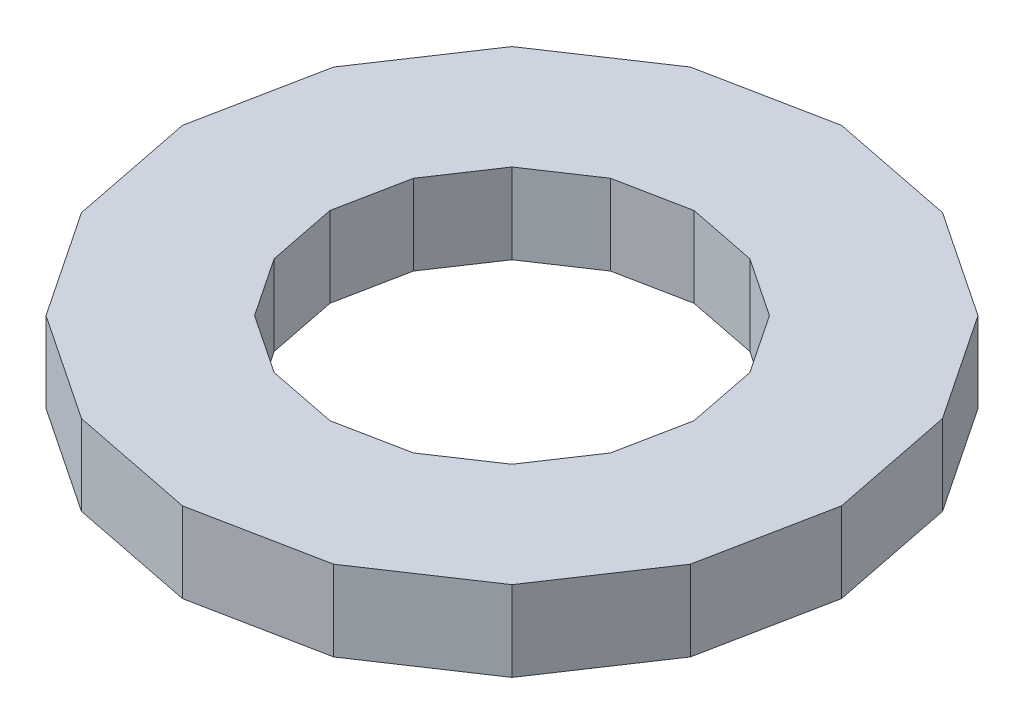
SolidWorks part; units mm, degrees
ref_plane "Front Plane" through (0, 0, 0) normal (0, 0, 1) x (1, 0, 0)
ref_plane "Top Plane" through (0, 0, 0) normal (0, 1, 0) x (1, 0, 0)
ref_plane "Right Plane" through (0, 0, 0) normal (1, 0, 0) x (0, 0, -1)
sketch "Sketch2" plane through (0, 0, 0) normal (0, 1, 0) x (1, 0, 0)
  line L0 (0, 0) -> (-43.1559, 0) construction
  line L1 (-78.1177, 0) -> (-72.1713, -29.8943)
  line L2 (-72.1713, -29.8943) -> (-55.2375, -55.2375)
  line L3 (-55.2375, -55.2375) -> (-29.8943, -72.1713)
  line L4 (-29.8943, -72.1713) -> (0, -78.1177)
  line L5 (0, -78.1177) -> (29.8943, -72.1713)
  line L6 (29.8943, -72.1713) -> (55.2375, -55.2375)
  line L7 (55.2375, -55.2375) -> (72.1713, -29.8943)
  line L8 (72.1713, -29.8943) -> (78.1177, 0)
  line L9 (78.1177, 0) -> (72.1713, 29.8943)
  line L10 (72.1713, 29.8943) -> (55.2375, 55.2375)
  line L11 (55.2375, 55.2375) -> (29.8943, 72.1713)
  line L12 (29.8943, 72.1713) -> (0, 78.1177)
  line L13 (0, 78.1177) -> (-29.8943, 72.1713)
  line L14 (-29.8943, 72.1713) -> (-55.2375, 55.2375)
  line L15 (-55.2375, 55.2375) -> (-72.1713, 29.8943)
  line L16 (-72.1713, 29.8943) -> (-78.1177, 0)
  line L17 (-43.1559, 0) -> (-39.8708, -16.515)
  line L18 (-39.8708, -16.515) -> (-30.5158, -30.5158)
  line L19 (-30.5158, -30.5158) -> (-16.515, -39.8708)
  line L20 (-16.515, -39.8708) -> (0, -43.1559)
  line L21 (0, -43.1559) -> (16.515, -39.8708)
  line L22 (16.515, -39.8708) -> (30.5158, -30.5158)
  line L23 (30.5158, -30.5158) -> (39.8708, -16.515)
  line L24 (39.8708, -16.515) -> (43.1559, 0)
  line L25 (43.1559, 0) -> (39.8708, 16.515)
  line L26 (39.8708, 16.515) -> (30.5158, 30.5158)
  line L27 (30.5158, 30.5158) -> (16.515, 39.8708)
  line L28 (16.515, 39.8708) -> (0, 43.1559)
  line L29 (0, 43.1559) -> (-16.515, 39.8708)
  line L30 (-16.515, 39.8708) -> (-30.5158, 30.5158)
  line L31 (-30.5158, 30.5158) -> (-39.8708, 16.515)
  line L32 (-39.8708, 16.515) -> (-43.1559, 0)
  line L33 (-78.1177, 0) -> (-43.1559, 0) construction
  circle A0 centre (0, 0) radius 76.6167 construction
  circle A1 centre (0, 0) radius 42.3267 construction
  dimension "D1" = 30.48
  dimension "D2" = 34.29
extrude "Boss-Extrude2" add sketch "Sketch2" along normal blind 19.05
